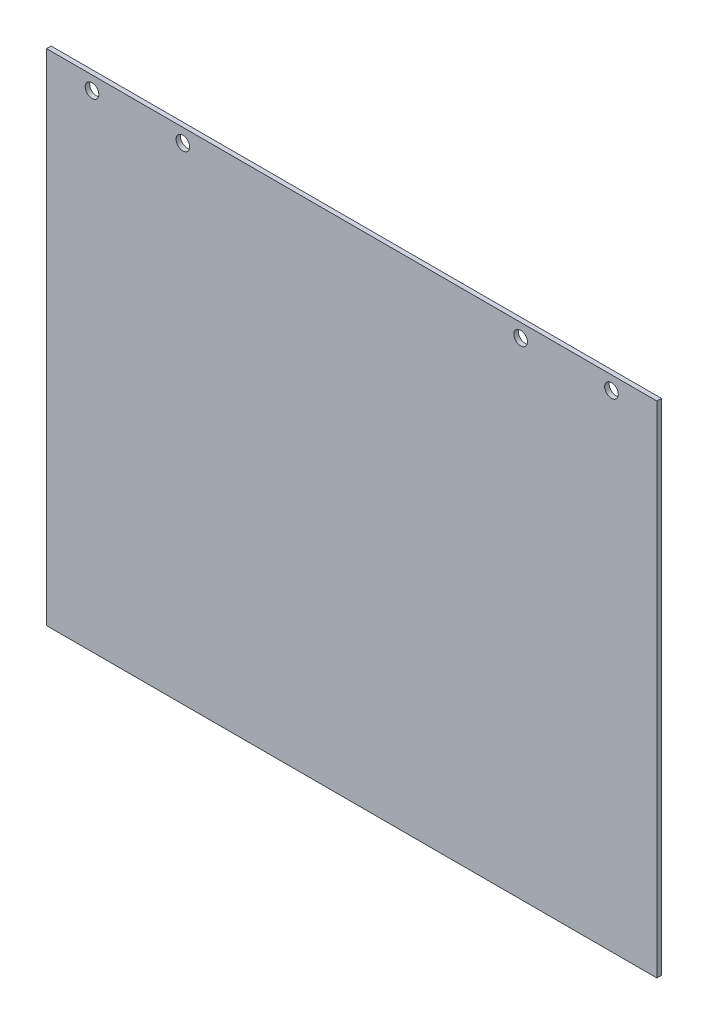
SolidWorks part; units mm, degrees
ref_plane "前视基准面" through (0, 0, 0) normal (0, 0, 1) x (1, 0, 0)
ref_plane "上视基准面" through (0, 0, 0) normal (0, 1, 0) x (1, 0, 0)
ref_plane "右视基准面" through (0, 0, 0) normal (1, 0, 0) x (0, 0, -1)
sketch "草图1" plane through (0, 0, 0) normal (0, 0, 1) x (1, 0, 0)
  line L0 (67.1751, 0) -> (67.1751, -67.1751) construction
  line L1 (0, 0) -> (134.3503, 0)
  line L2 (0, 0) -> (0, 110)
  line L3 (0, 110) -> (134.3503, 110)
  line L4 (134.3503, 0) -> (134.3503, 110)
  line L5 (67.1751, -67.1751) -> (0, 0) construction
  line L6 (67.1751, -67.1751) -> (134.3503, 0) construction
  line L7 (67.1751, 110) -> (67.1751, 0) construction
  line L8 (10, 110) -> (10, 107) construction
  line L9 (10, 107) -> (30, 107) construction
  circle A0 centre (10, 107) radius 1.5
  circle A1 centre (30, 107) radius 1.5
  circle A2 centre (104.3503, 107) radius 1.5
  circle A3 centre (124.3503, 107) radius 1.5
  dimension "D3" = 3
  dimension "D1" = 95
  dimension "D2" = 110
  dimension "D4" = 3
  dimension "D5" = 10
  dimension "D6" = 20
extrude "凸台-拉伸1" add sketch "草图1" along normal blind 1
